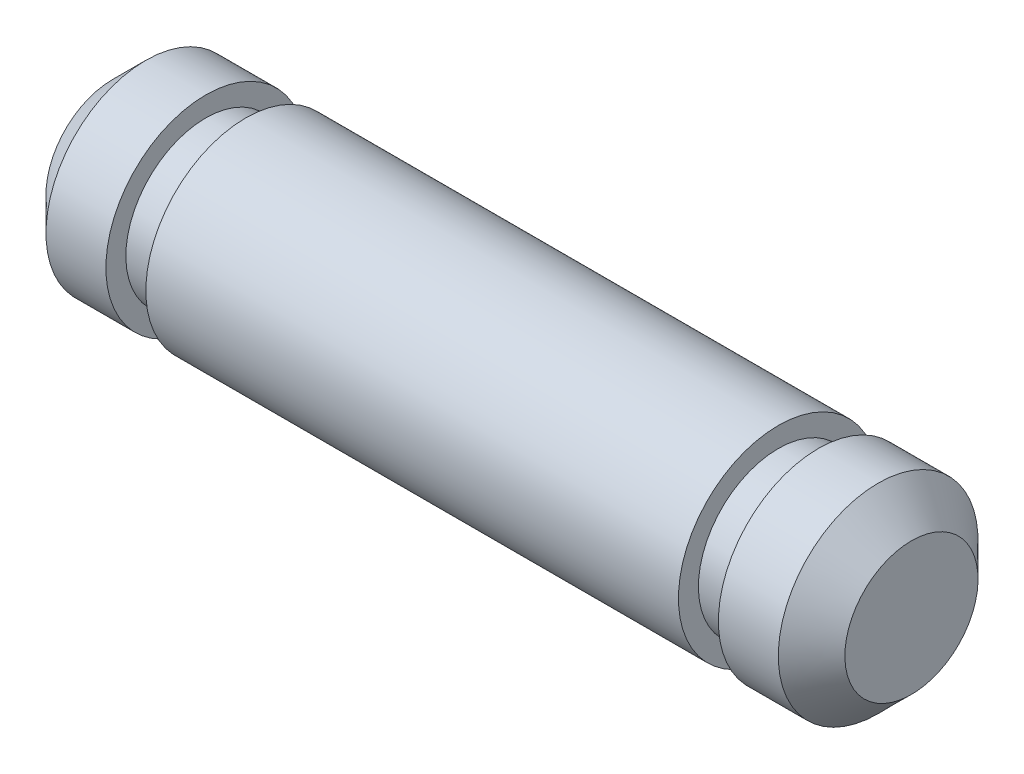
SolidWorks part; units mm, degrees
ref_plane "前视基准面" through (0, 0, 0) normal (0, 0, 1) x (1, 0, 0)
ref_plane "上视基准面" through (0, 0, 0) normal (0, 1, 0) x (1, 0, 0)
ref_plane "右视基准面" through (0, 0, 0) normal (1, 0, 0) x (0, 0, -1)
sketch "草图1" plane through (0, 0, 0) normal (0, 0, 1) x (1, 0, 0)
  line L0 (6, 0) -> (-6, 0)
  line L1 (-6, 0) -> (-6, 1)
  line L2 (4.6, 1.5) -> (4.6, 1.2)
  line L3 (-5.5, 1.5) -> (-4.6, 1.5)
  line L4 (-4.6, 1.5) -> (-4.6, 1.2)
  line L5 (-4.6, 1.2) -> (-4, 1.2)
  line L6 (-4, 1.2) -> (-4, 1.5)
  line L7 (-4, 1.5) -> (4, 1.5)
  line L8 (0, 1.5) -> (0, 0) construction
  line L9 (4, 1.2) -> (4, 1.5)
  line L10 (6, 0) -> (6, 1)
  line L11 (5.5, 1.5) -> (4.6, 1.5)
  line L12 (4.6, 1.2) -> (4, 1.2)
  line L13 (-6, 1) -> (-5.5, 1.5)
  line L14 (6, 1) -> (5.5, 1.5)
  point P4 (0, 0)
  point P15 (-6, 1.5)
  point P18 (6, 1.5)
  dimension "D1" = 0.6
  dimension "D2" = 8
  dimension "D3" = 12
  dimension "D4" = 1.5
  dimension "D5" = 0.3
revolve "旋转1" add sketch "草图1" angle 360 about L0
